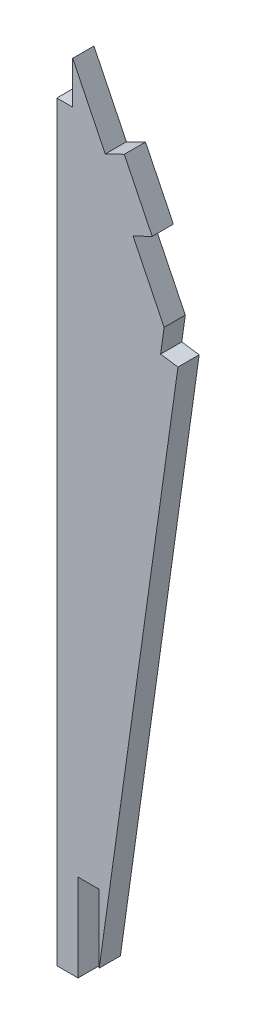
SolidWorks part; units mm, degrees
ref_plane "前视基准面" through (0, 0, 0) normal (0, 0, 1) x (1, 0, 0)
ref_plane "上视基准面" through (0, 0, 0) normal (0, 1, 0) x (1, 0, 0)
ref_plane "右视基准面" through (0, 0, 0) normal (1, 0, 0) x (0, 0, -1)
sketch "草图1" plane through (0, 0, 0) normal (0, 0, 1) x (1, 0, 0)
  line L0 (6.1731, 80.743) -> (6.1731, 76.743)
  line L1 (6.1731, 76.743) -> (4.6731, 76.743)
  line L2 (4.6731, 76.743) -> (4.6731, 5.8351)
  line L3 (4.6731, 5.8351) -> (6.6731, 5.8351)
  line L4 (6.6731, 5.8351) -> (6.6731, 14.0851)
  line L5 (6.6731, 14.0851) -> (8.6731, 14.0851)
  line L6 (8.6731, 14.0851) -> (8.6731, 7.6404)
  line L7 (8.6731, 7.6404) -> (16.1045, 60.4763)
  line L8 (16.1045, 60.4763) -> (14.463, 60.7075)
  line L9 (14.463, 60.7075) -> (14.795, 63.0654)
  line L10 (6.1731, 80.743) -> (9.2417, 74.4515)
  line L11 (9.2417, 74.4515) -> (11.0392, 75.3282)
  line L12 (11.0392, 75.3282) -> (13.6695, 69.9355)
  line L13 (13.6695, 69.9355) -> (11.8719, 69.0587)
  line L14 (11.8719, 69.0587) -> (14.795, 63.0654)
extrude "凸台-拉伸1" add sketch "草图1" along normal blind 2
